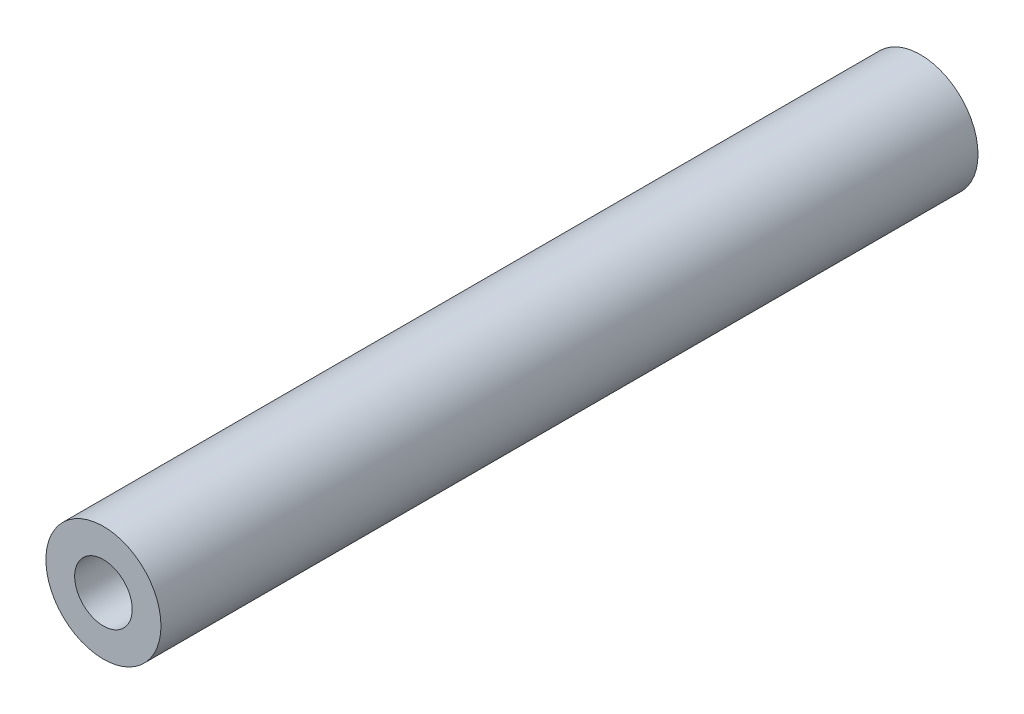
SolidWorks part; units mm, degrees
ref_plane "前视基准面" through (0, 0, 0) normal (0, 0, 1) x (1, 0, 0)
ref_plane "上视基准面" through (0, 0, 0) normal (0, 1, 0) x (1, 0, 0)
ref_plane "右视基准面" through (0, 0, 0) normal (1, 0, 0) x (0, 0, -1)
sketch "草图1" plane through (0, 0, 0) normal (0, 0, 1) x (1, 0, 0)
  circle A0 centre (0, 0) radius 2.5
  circle A1 centre (0, 0) radius 5
  dimension "D1" = 5
  dimension "D2" = 10
extrude "凸台-拉伸1" add sketch "草图1" along normal blind 71
